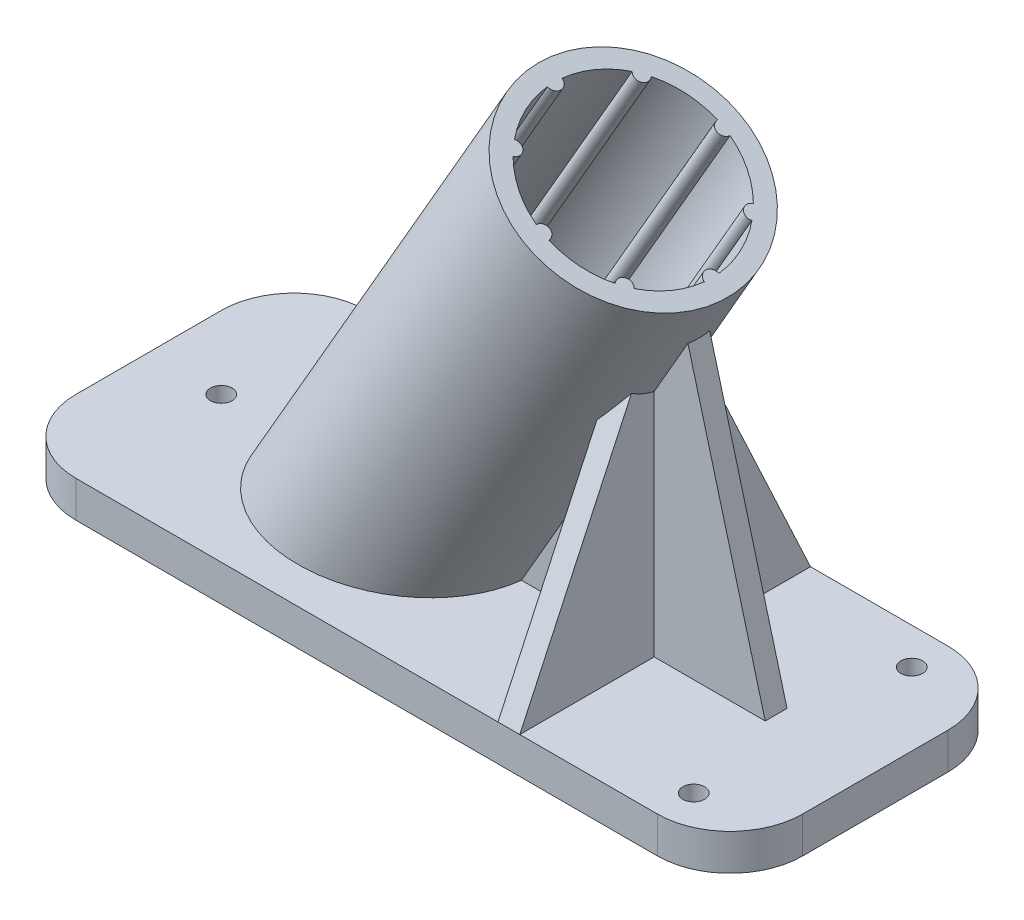
SolidWorks part; units mm, degrees
ref_plane "Front Plane" through (0, 0, 0) normal (0, 0, 1) x (1, 0, 0)
ref_plane "Top Plane" through (0, 0, 0) normal (0, 1, 0) x (1, 0, 0)
ref_plane "Right Plane" through (0, 0, 0) normal (1, 0, 0) x (0, 0, -1)
sketch "Sketch1" plane through (0, 0, 0) normal (0, 1, 0) x (1, 0, 0)
  line L1 (40, 20) -> (-40, 20)
  line L2 (50, 10) -> (50, -10)
  line L3 (40, -20) -> (-40, -20)
  line L4 (-50, 10) -> (-50, -10)
  line L5 (50, 20) -> (-50, -20) construction
  line L6 (50, -20) -> (-50, 20) construction
  arc A0 (50, -10) -> (40, -20) centre (40, -10) cw
  arc A1 (40, 20) -> (50, 10) centre (40, 10) cw
  arc A2 (-40, -20) -> (-50, -10) centre (-40, -10) cw
  arc A3 (-40, 20) -> (-50, 10) centre (-40, 10) ccw
  point P0 (0, 0)
  dimension "D3" = 10
  dimension "D1" = 100
  dimension "D2" = 40
extrude "Boss-Extrude1" add sketch "Sketch1" along normal blind 5
ref_plane "Plane1" through (14.6651, 25.4006, 0) normal (0.5, 0.866, 0) x (0, 0, -1)
ref_plane "Plane2" through (29.6651, 51.3814, 0) normal (0.5, 0.866, 0) x (0, 0, -1)
sketch "Sketch2" plane through (29.6651, 51.3814, 0) normal (0.5, 0.866, 0) x (0, 0, -1)
  circle A0 centre (0, 15) radius 15
  circle A1 centre (0, 15) radius 12.5
  dimension "D1" = 30
  dimension "D3" = 25
  dimension "D2" = 15
extrude "Boss-Extrude2" add sketch "Sketch2" against normal up to surface (70.8771 mm away)
sketch "Sketch3" plane through (29.6651, 51.3814, 0) normal (0.5, 0.866, 0) x (0.866, -0.5, 0)
  circle A0 centre (-2.5, 0) radius 1
  circle A1 centre (-15, 0) radius 12.5 construction
  circle A2 centre (-15, 0) radius 12.5 construction
  circle A3 centre (-6.1612, -8.8388) radius 1
  circle A4 centre (-15, -12.5) radius 1
  circle A5 centre (-23.8388, -8.8388) radius 1
  circle A6 centre (-27.5, 0) radius 1
  circle A7 centre (-23.8388, 8.8388) radius 1
  circle A8 centre (-15, 12.5) radius 1
  circle A9 centre (-6.1612, 8.8388) radius 1
  point P23 (-15, 0)
  dimension "D1" = 2
  dimension "D3" = 25
  dimension "D2" = 8
extrude "Boss-Extrude3" add sketch "Sketch3" against normal up to surface (55.5774 mm away)
sketch "Sketch4" plane through (0, 0, 0) normal (0, 0, 1) x (1, 0, 0)
  line L0 (28.3013, 35) -> (35, 10)
  line L1 (50, 5) -> (50, 0) construction
  line L2 (-40, 5) -> (40, 5) construction
  dimension "D1" = 25
  dimension "D2" = 15
  dimension "D3" = 75
  dimension "D4" = 5
rib "Rib1" sketch "Sketch4" sketch "Sketch4" thickness 3 extrusion direction parallel to sketch draft on no parameters "D1"=3
ref_plane "Plane3" through (19.5698, 0, 0) normal (1, 0, 0) x (0, 0, -1)
sketch "Sketch5" plane through (19.5698, 0, 0) normal (1, 0, 0) x (0, 0, -1)
  line L0 (-1.5, 44.678) -> (-20, 5)
rib "Rib2" sketch "Sketch5" sketch "Sketch5" thickness 3 extrusion direction parallel to sketch draft on no parameters "D1"=3
mirror "Mirror2" about plane through (0, 0, 0) normal (0, 0, 1) of "Rib2"
sketch "Sketch6" plane through (0, 0, 0) normal (0, -1, 0) x (-1, 0, 0)
  line L1 (-40, -15) -> (40, -15) construction
  line L2 (-40, -15) -> (-40, 15) construction
  line L3 (-40, 15) -> (40, 15) construction
  line L4 (40, -15) -> (40, 15) construction
  line L5 (-40, -15) -> (40, 15) construction
  line L6 (-40, 15) -> (40, -15) construction
  circle A0 centre (-40, 15) radius 1.5
  circle A1 centre (-40, -15) radius 1.5
  circle A2 centre (40, 0) radius 1.5
  point P0 (0, 0)
  dimension "D3" = 3
  dimension "D4" = 3
  dimension "D5" = 3
  dimension "D1" = 80
  dimension "D2" = 30
extrude "Cut-Extrude1" cut sketch "Sketch6" against normal up to surface (5 mm away) up to face at (-14.0817, 5, 0)
